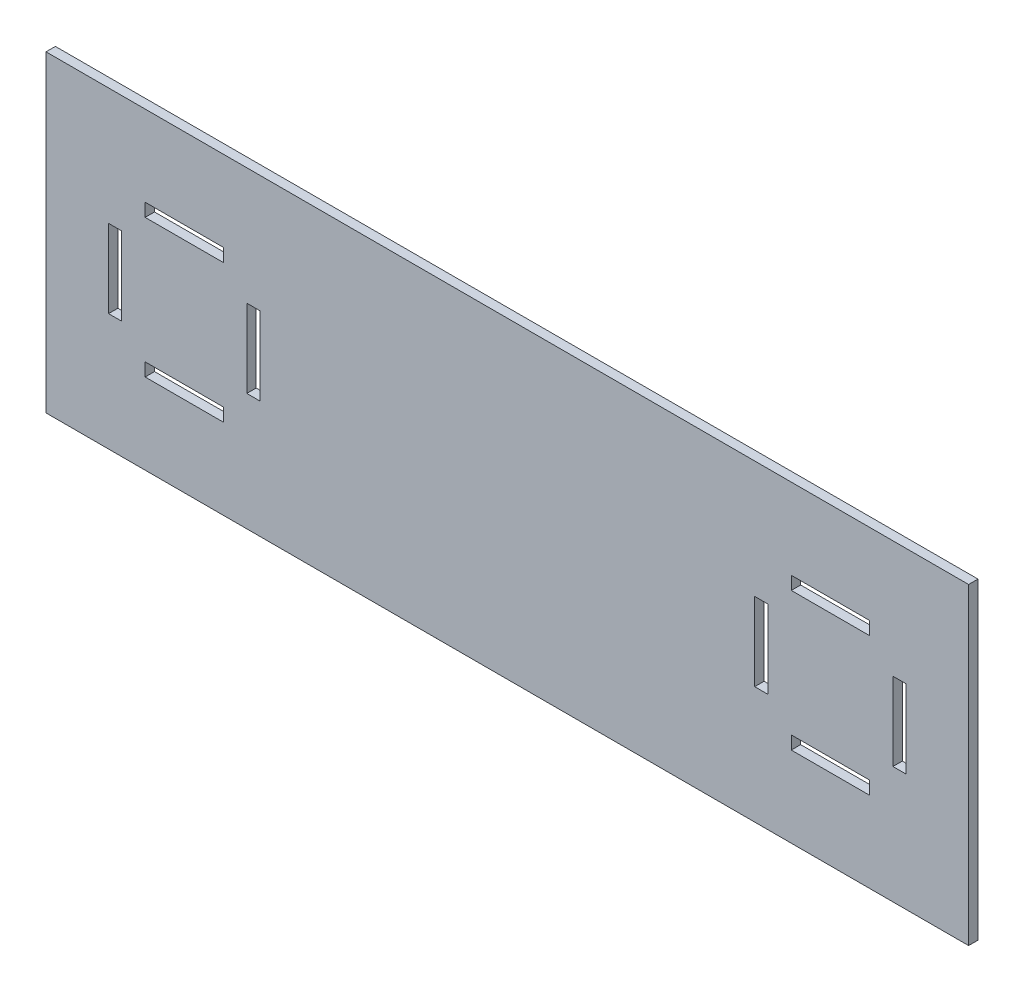
SolidWorks part; units mm, degrees
ref_plane "Plano frontal" through (0, 0, 0) normal (0, 0, 1) x (1, 0, 0)
ref_plane "Plano superior" through (0, 0, 0) normal (0, 1, 0) x (1, 0, 0)
ref_plane "Plano direito" through (0, 0, 0) normal (1, 0, 0) x (0, 0, -1)
sketch "Esboço1" plane through (0, 0, 0) normal (0, 0, 1) x (1, 0, 0)
  line L1 (-147.5, -50) -> (147.5, -50)
  line L2 (-147.5, -50) -> (-147.5, 50)
  line L3 (-147.5, 50) -> (147.5, 50)
  line L4 (147.5, -50) -> (147.5, 50)
  line L5 (-147.5, -50) -> (147.5, 50) construction
  line L6 (-147.5, 50) -> (147.5, -50) construction
  point P0 (0, 0)
  dimension "D1" = 295
  dimension "D2" = 100
extrude "Ressalto-extrusão1" add sketch "Esboço1" along normal blind 3
sketch "Esboço2" plane through (0, 0, 3) normal (0, 0, 1) x (1, 0, 0)
  line L0 (-147.5, 0) -> (147.5, 0) construction
  line L1 (-147.5, 50) -> (-147.5, -50) construction
  line L2 (147.5, -50) -> (147.5, 50) construction
  line L3 (0, 50) -> (0, -50) construction
  line L4 (147.5, 50) -> (-147.5, 50) construction
  line L5 (-147.5, -50) -> (147.5, -50) construction
  line L6 (-103.3, 50) -> (-103.3, -50) construction
  line L11 (127.5, 12.5) -> (123.3, 12.5)
  line L12 (123.3, -12.5) -> (123.3, 12.5)
  line L13 (-83.3, -12.5) -> (-79.1, -12.5)
  line L14 (-83.3, -12.5) -> (-83.3, 12.5)
  line L15 (-83.3, 12.5) -> (-79.1, 12.5)
  line L16 (-79.1, -12.5) -> (-79.1, 12.5)
  line L17 (-83.3, -12.5) -> (-79.1, 12.5) construction
  line L18 (-83.3, 12.5) -> (-79.1, -12.5) construction
  line L19 (-127.5, -12.5) -> (-123.3, -12.5)
  line L20 (-127.5, -12.5) -> (-127.5, 12.5)
  line L21 (-127.5, 12.5) -> (-123.3, 12.5)
  line L22 (-123.3, -12.5) -> (-123.3, 12.5)
  line L23 (-127.5, -12.5) -> (-123.3, 12.5) construction
  line L24 (-127.5, 12.5) -> (-123.3, -12.5) construction
  line L25 (-115.8, 20) -> (-90.8, 20)
  line L26 (-115.8, -24.2) -> (-90.8, -24.2)
  line L27 (-115.8, -24.2) -> (-115.8, -20)
  line L28 (-115.8, -20) -> (-90.8, -20)
  line L29 (-90.8, -24.2) -> (-90.8, -20)
  line L30 (-115.8, -24.2) -> (-90.8, -20) construction
  line L31 (-115.8, -20) -> (-90.8, -24.2) construction
  line L32 (-90.8, 24.2) -> (-90.8, 20)
  line L33 (-115.8, 24.2) -> (-90.8, 24.2)
  line L34 (-115.8, 24.2) -> (-115.8, 20)
  line L35 (127.5, -12.5) -> (123.3, -12.5)
  line L36 (127.5, -12.5) -> (127.5, 12.5)
  line L37 (83.3, 12.5) -> (79.1, 12.5)
  line L38 (79.1, -12.5) -> (79.1, 12.5)
  line L39 (83.3, -12.5) -> (79.1, -12.5)
  line L40 (83.3, -12.5) -> (83.3, 12.5)
  line L41 (115.8, -20) -> (90.8, -20)
  line L42 (90.8, -24.2) -> (90.8, -20)
  line L43 (115.8, -24.2) -> (90.8, -24.2)
  line L44 (115.8, -24.2) -> (115.8, -20)
  line L45 (115.8, 24.2) -> (115.8, 20)
  line L46 (115.8, 24.2) -> (90.8, 24.2)
  line L47 (90.8, 24.2) -> (90.8, 20)
  line L48 (115.8, 20) -> (90.8, 20)
  point P13 (-90.8, -22.1)
  point P17 (-81.2, 0)
  point P22 (-125.4, 0)
  point P29 (-103.3, -22.1)
  dimension "D1" = 25
  dimension "D2" = 4.2
  dimension "D3" = 4.2
  dimension "D4" = 40
  dimension "D5" = 40
  dimension "D6" = 20
  dimension "D7" = 25
  dimension "D8" = 20
extrude "Corte-extrusão1" cut sketch "Esboço2" against normal through all
